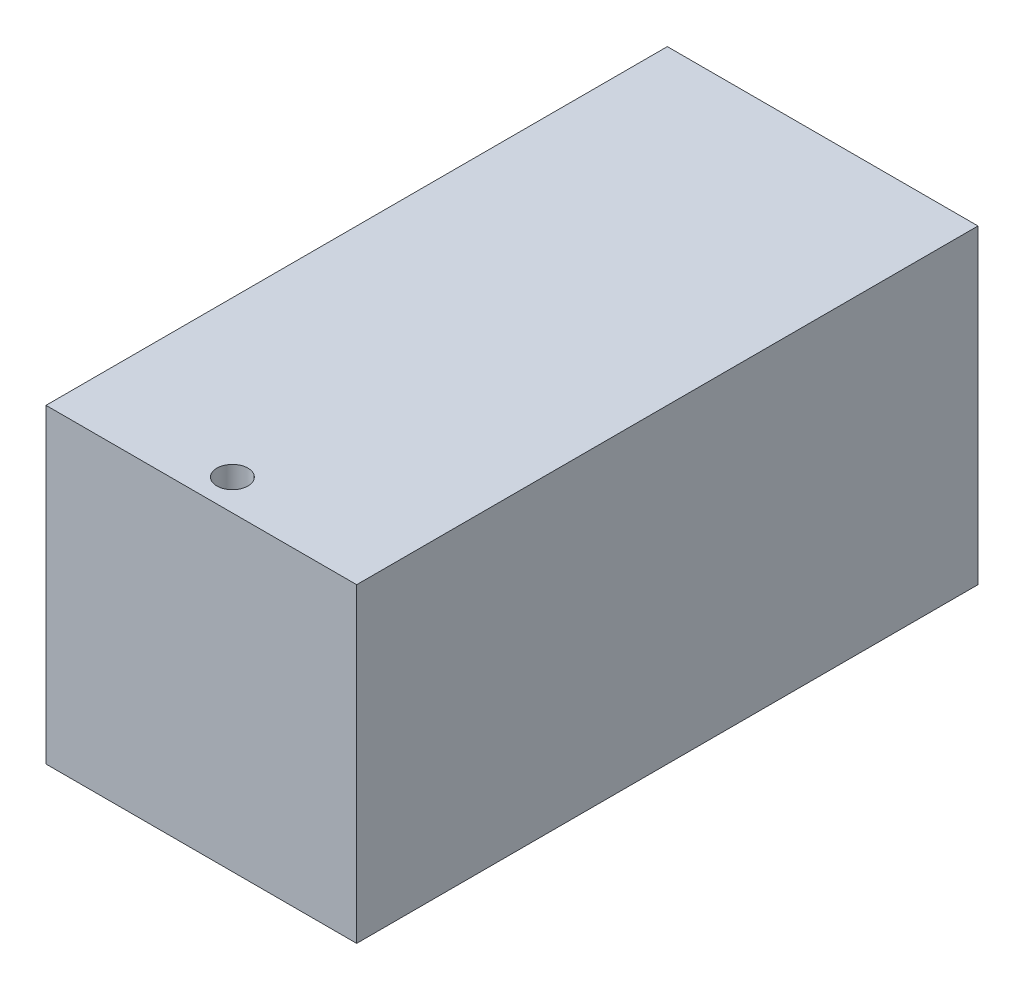
SolidWorks part; units mm, degrees
ref_plane "Front Plane" through (0, 0, 0) normal (0, 0, 1) x (1, 0, 0)
ref_plane "Top Plane" through (0, 0, 0) normal (0, 1, 0) x (1, 0, 0)
ref_plane "Right Plane" through (0, 0, 0) normal (1, 0, 0) x (0, 0, -1)
sketch "Sketch1" plane through (0, 0, 0) normal (0, 0, 1) x (1, 0, 0)
  line L1 (0, 0) -> (50, 0)
  line L2 (0, 0) -> (0, -50)
  line L3 (0, -50) -> (50, -50)
  line L4 (50, 0) -> (50, -50)
  dimension "D1" = 50
extrude "Boss-Extrude1" add sketch "Sketch1" along normal blind 100
sketch "Sketch2" plane through (0, 0, 0) normal (0, 1, 0) x (1, 0, 0)
  line L0 (50, -100) -> (0, -100) construction
  circle A0 centre (25, -95) radius 2.5
  point P4 (0, 0)
  point P5 (25, -100)
  dimension "D1" = 5
  dimension "D2" = 5
extrude "Cut-Extrude1" cut sketch "Sketch2" against normal through all
sketch "Sketch3" plane through (0, 0, 0) normal (0, 0, -1) x (-1, 0, 0)
  line L0 (-25, 0) -> (-25, -25) construction
  line L1 (-50, 0) -> (0, 0) construction
  line L2 (-25, -25) -> (-50, -25) construction
  line L3 (-50, -50) -> (-50, 0) construction
